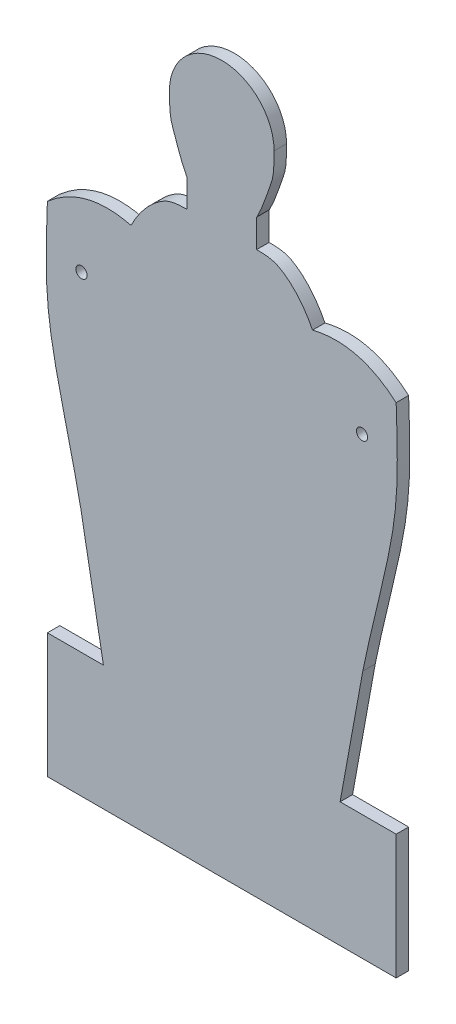
SolidWorks part; units mm, degrees
material "Papel canelado"
ref_plane "Plano frontal" through (0, 0, 0) normal (0, 0, 1) x (1, 0, 0)
ref_plane "Plano superior" through (0, 0, 0) normal (0, 1, 0) x (1, 0, 0)
ref_plane "Plano direito" through (0, 0, 0) normal (1, 0, 0) x (0, 0, -1)
sketch "Esboço1" plane through (0, 0, 0) normal (0, 0, 1) x (1, 0, 0)
  line L0 (0, -2307.3244) -> (0, 113058.8949) construction
  line L1 (-70, 0) -> (70, 0)
  line L3 (-70, 0) -> (-70, 50)
  line L6 (-70, 50) -> (-47.5, 50)
  line L7 (-47.5, 50) -> (-56.606, 100)
  line L8 (-14, 236.4884) -> (-14, 219.6)
  line L10 (0, 235) -> (0, 230.8) construction
  line L14 (14, 236.4884) -> (14, 219.6)
  line L15 (47.5, 50) -> (56.606, 100)
  line L16 (70, 50) -> (47.5, 50)
  line L17 (70, 0) -> (70, 50)
  arc A0 (21, 263) -> (-21, 263) centre (0, 263) ccw
  arc A2 (-14, 236.4884) -> (-14.1721, 236.7231) centre (-13.2883, 237.1909) cw
  arc A3 (14, 236.4884) -> (14.1721, 236.7231) centre (13.2883, 237.1909) ccw
  spline S0 degree 3 poles (-56.606, 100) (-58.8229, 111.2305) (-70.6241, 157.6532) (-70.9835, 170.9484) (-70, 200) knots 0 0 0 0 0.304799 1 1 1 1
  spline S1 degree 2 poles (-70, 200) (-54.9402, 213.0776) (-36.4, 208.4) knots 0 0 0 1 1 1
  spline S2 degree 3 poles (-36.4, 208.4) (-36.3844, 208.4081) (-31.8537, 218.695) (-19.6252, 225.4968) (-14.2871, 225.1266) (-14, 225.2) knots 0 0 0 0 0.552885 0.635199 0.823141 0.823141 0.823141 0.823141
  spline S3 degree 3 poles (-14.1721, 236.7231) (-16.4387, 241.0051) (-19.848, 251.9613) (-20.9809, 253.9334) (-21, 263) knots 0.009276 0.009276 0.009276 0.009276 0.37796 0.746645 0.746645 0.746645 0.746645
  spline S4 degree 3 poles (14.1721, 236.7231) (16.4387, 241.0051) (19.848, 251.9613) (20.9809, 253.9334) (21, 263) knots 0.009276 0.009276 0.009276 0.009276 0.37796 0.746645 0.746645 0.746645 0.746645
  spline S5 degree 3 poles (36.4, 208.4) (36.3844, 208.4081) (31.8537, 218.695) (19.6252, 225.4968) (14.2871, 225.1266) (14, 225.2) knots 0 0 0 0 0.552885 0.635199 0.823141 0.823141 0.823141 0.823141
  spline S6 degree 2 poles (70, 200) (54.9402, 213.0776) (36.4, 208.4) knots 0 0 0 1 1 1
  spline S7 degree 3 poles (56.606, 100) (58.8229, 111.2305) (70.6241, 157.6532) (70.9835, 170.9484) (70, 200) knots 0 0 0 0 0.304799 1 1 1 1
  point P19 (0, 230.8)
  point P22 (0, 284)
  point P52 (0, 0)
  dimension "D7" = 42
  dimension "D14" = 1
  dimension "D17" = 27.2
  dimension "D1" = 140
  dimension "D2" = 50
  dimension "D3" = 95
  dimension "D4" = 50
  dimension "D5" = 150
  dimension "D6" = 140
  dimension "D8" = 28
  dimension "D9" = 33.6
  dimension "D10" = 53.2
  dimension "D11" = 84
  dimension "D12" = 16.8
  dimension "D13" = 8.4
  dimension "D15" = 5.6
extrude "Ressalto-extrusão1" add sketch "Esboço1" along normal blind 5
sketch "Esboço3" plane through (0, 0, 5) normal (0, 0, 1) x (1, 0, 0)
  line L0 (-70, 50) -> (-47.5, 50) construction
  line L1 (-70, 0) -> (-70, 50) construction
  line L2 (0, -1000) -> (0, 49000) construction
  circle A0 centre (-56.3, 182.2) radius 2.25
  circle A1 centre (56.3, 182.2) radius 2.25
  dimension "D1" = 132.2
  dimension "D2" = 13.7
  dimension "D3" = 4.5
extrude "Corte-extrusão1" cut sketch "Esboço3" against normal through all
